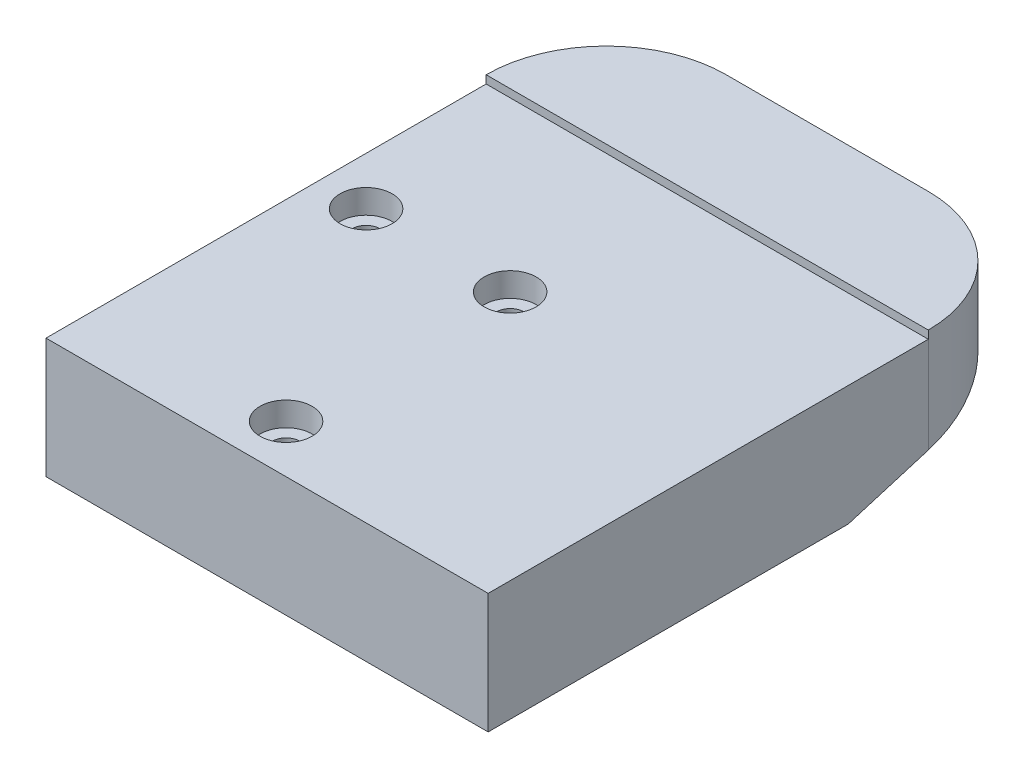
SolidWorks part; units mm, degrees
material "ABS"
ref_plane "Front Plane" through (0, 0, 0) normal (0, 0, 1) x (1, 0, 0)
ref_plane "Top Plane" through (0, 0, 0) normal (0, 1, 0) x (1, 0, 0)
ref_plane "Right Plane" through (0, 0, 0) normal (1, 0, 0) x (0, 0, -1)
sketch "Sketch1" plane through (0, 0, 0) normal (0, 1, 0) x (1, 0, 0)
  line L1 (0, 0) -> (55.25, 0)
  line L2 (0, 0) -> (0, 55)
  line L3 (15, 70) -> (40.25, 70)
  line L4 (55.25, 0) -> (55.25, 55)
  arc A3 (40.25, 70) -> (55.25, 55) centre (40.25, 55) cw
  arc A4 (0, 55) -> (15, 70) centre (15, 55) cw
  circle A6 centre (24, 6) radius 1.6 construction
  circle A7 centre (6, 34) radius 1.6 construction
  circle A8 centre (24, 34) radius 1.6 construction
  dimension "D3" = 15
  dimension "D1" = 70
  dimension "D2" = 55.25
extrude "Boss-Extrude1" add sketch "Sketch1" along normal blind 15
hole_wizard "CBORE for M3 SHCS1" positions "Sketch2" profile "Sketch3" counterbore size "M3" standard "ANSI Metric" end condition through all
sketch "Sketch2" plane through (0, 15, 0) normal (0, 1, 0) x (1, 0, 0)
  point P0 (6, 34)
  point P3 (24, 34)
  point P6 (24, 6)
sketch "Sketch3" plane through (6, 15, -34) normal (1, 0, 0) x (0, 0, 1)
  line L0 (0, 0) -> (0, 15)
  line L1 (0, 15) -> (1.7, 15)
  line L3 (1.7, 15) -> (1.7, 3)
  line L4 (1.7, 3) -> (3.25, 3)
  line L5 (3.25, 3) -> (3.25, 0)
  line L7 (3.25, 0) -> (0, 0)
  line L11 (0, -6.35) -> (0, 107.95) construction
  dimension "Thru Hole Dia." = 3.4
  dimension "Thru Hole Depth" = 15
  dimension "C'Bore Dia." = 6.5
  dimension "C'Bore Depth" = 3
sketch "Sketch4" plane through (0, 0, 0) normal (-1, 0, 0) x (0, 0, 1)
  line L0 (-70, 0) -> (-45, 0)
  line L1 (-45, 0) -> (-70, 7.5)
  line L2 (-70, 7.5) -> (-70, 0)
  line L4 (-70, 15) -> (-70, 0) construction
  line L5 (-55, 0) -> (0, 0) construction
  dimension "D1" = 7.5
  dimension "D2" = 25
extrude "Cut-Extrude1" cut sketch "Sketch4" against normal up to next
sketch "Sketch5" plane through (0, 15, 0) normal (0, 1, 0) x (1, 0, 0)
  line L1 (-5.2729, 55) -> (60.5229, 55)
  line L4 (0, 55) -> (0, 0)
  line L5 (0, 0) -> (55.25, 0)
  line L6 (55.25, 0) -> (55.25, 55)
  line L7 (40.25, 70) -> (15, 70)
  line L11 (40.25, 70) -> (15, 70)
  arc A2 (55.25, 55) -> (40.25, 70) centre (40.25, 55) ccw
  arc A3 (15, 70) -> (0, 55) centre (15, 55) ccw
  arc A4 (55.25, 55) -> (40.25, 70) centre (40.25, 55) ccw
  arc A5 (15, 70) -> (0, 55) centre (15, 55) ccw
  arc M13 (55.25, 55) -> (40.25, 70) centre (40.25, 55) ccw
  line M14 (40.25, 70) -> (15, 70)
  arc M15 (15, 70) -> (0, 55) centre (15, 55) ccw
  dimension "D2" = 15
  dimension "D1" = 0
extrude "Boss-Extrude2" add sketch "Sketch5" along normal blind 1 contours L1 M15 M13 M14
ref_plane "Plane1" through (27.625, 0, 0) normal (-1, 0, 0) x (0, 0, 1)
sketch "Sketch7" plane through (0, 16, 0) normal (0, 1, 0) x (1, 0, 0)
  line L0 (0, 45) -> (22.625, 70)
  line L1 (22.625, 70) -> (0, 70)
  line L2 (0, 70) -> (0, 45)
  line L4 (0, 55) -> (0, 0) construction
  line L5 (27.625, 8.25) -> (27.625, -8.25) construction
  line L6 (55.25, 45) -> (32.625, 70)
  line L7 (55.25, 70) -> (55.25, 45)
  line L8 (32.625, 70) -> (55.25, 70)
  line L9 (40.25, 70) -> (15, 70) construction
  dimension "D1" = 5
  dimension "D2" = 25
sketch "Sketch9" plane through (55.25, 0, 0) normal (1, 0, 0) x (0, 0, -1)
  line L0 (69.2, 16.1) -> (70, 16.1)
  line L1 (56, 16.1) -> (57.2, 16.1)
  line L3 (70, 16.1) -> (70, 17.9005)
  line L4 (57.2, 16.1) -> (57.5, 17)
  line L5 (57.5, 17) -> (58.7, 17)
  line L6 (58.7, 17) -> (59, 16.1)
  line L7 (59, 16.1) -> (60.2, 16.1)
  line L8 (60.2, 16.1) -> (60.5, 17)
  line L9 (60.5, 17) -> (61.7, 17)
  line L10 (61.7, 17) -> (62, 16.1)
  line L11 (62, 16.1) -> (63.2, 16.1)
  line L12 (63.2, 16.1) -> (63.5, 17)
  line L13 (63.5, 17) -> (64.7, 17)
  line L14 (64.7, 17) -> (65, 16.1)
  line L15 (65, 16.1) -> (66.2, 16.1)
  line L16 (66.2, 16.1) -> (66.5, 17)
  line L17 (66.5, 17) -> (67.7, 17)
  line L18 (67.7, 17) -> (68, 16.1)
  line L19 (68, 16.1) -> (69.2, 16.1)
  line L20 (54.9735, 16.1) -> (56, 16.1)
  line L21 (70, 17.9005) -> (54.9735, 17.9005)
  line L31 (54.9735, 17.9005) -> (54.9735, 16.0998)
extrude "Texture2" [suppressed] cut sketch "Sketch9" against normal through all contours L21 L31 L20 L1 L4 L5 L6 L7 L8 L9 L10 L11 L12 L13 L14 L15 L16 L17 L18 L19 L0 L3
